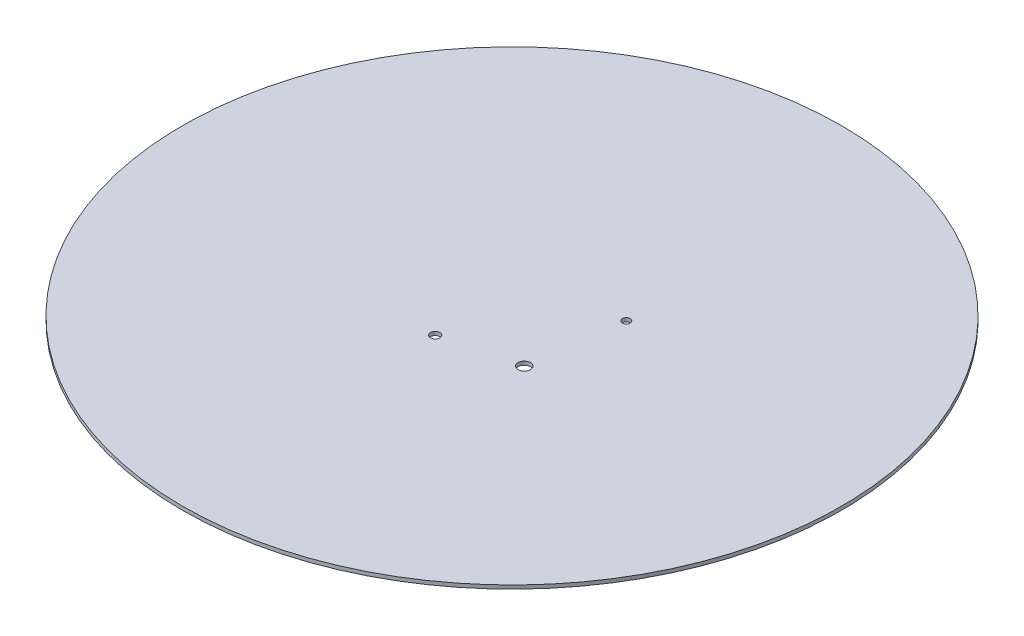
SolidWorks part; units mm, degrees
ref_plane "Front Plane" through (0, 0, 0) normal (0, 0, 1) x (1, 0, 0)
ref_plane "Top Plane" through (0, 0, 0) normal (0, 1, 0) x (1, 0, 0)
ref_plane "Right Plane" through (0, 0, 0) normal (1, 0, 0) x (0, 0, -1)
sketch "Sketch1" plane through (0, 0, 0) normal (0, 1, 0) x (1, 0, 0)
  circle A0 centre (0, 0) radius 273.3474
  circle A1 centre (-17.9887, -45.6841) radius 3.8601
  circle A2 centre (41.1365, -30.9579) radius 5.1175
  circle A3 centre (50.9122, 43.8953) radius 3.2179
extrude "Boss-Extrude1" add sketch "Sketch1" along normal blind 3
